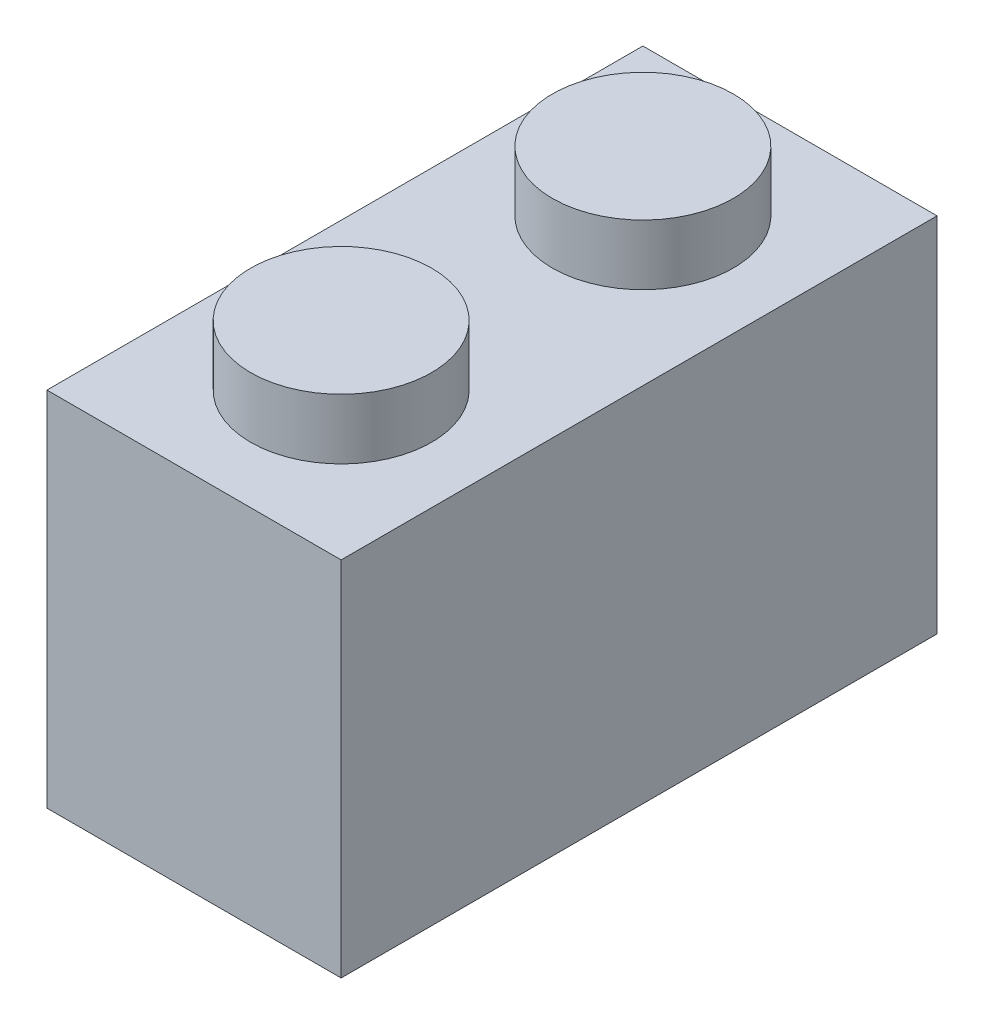
SolidWorks part; units mm, degrees
material "ABS"
ref_plane "Front Plane" through (0, 0, 0) normal (0, 0, 1) x (1, 0, 0)
ref_plane "Top Plane" through (0, 0, 0) normal (0, 1, 0) x (1, 0, 0)
ref_plane "Right Plane" through (0, 0, 0) normal (1, 0, 0) x (0, 0, -1)
sketch "Sketch1" plane through (0, 0, 0) normal (0, 0, 1) x (1, 0, 0)
  line L1 (0, 0) -> (7.8, 0)
  line L2 (0, 0) -> (0, 9.6)
  line L3 (0, 9.6) -> (7.8, 9.6)
  line L4 (7.8, 0) -> (7.8, 9.6)
  line L5 (0, 0) -> (7.8, 9.6) construction
  line L6 (0, 9.6) -> (7.8, 0) construction
  point P4 (3.9, 4.8)
  dimension "D1" = 7.8
  dimension "D2" = 9.6
extrude "Boss-Extrude1" add sketch "Sketch1" against normal blind 15.8
sketch "Sketch2" plane through (0, 9.6, 0) normal (0, 1, 0) x (1, 0, 0)
  line L0 (7.8, 0) -> (0, 0) construction
  circle A0 centre (3.9, 3.9) radius 2.4
  dimension "D1" = 4.8
  dimension "D2" = 3.9
  dimension "D3" = 3.9
extrude "Boss-Extrude2" add sketch "Sketch2" along normal blind 1.6
pattern_linear "LPattern1" count 2 spacing 8 along (0, 0, -1) count 4 spacing 8 along (-1, 0, 0) of "Boss-Extrude2"
shell "Shell1" thickness 1.2
sketch "Sketch4" plane through (0, 8.4, 0) normal (0, -1, 0) x (1, 0, 0)
  line L0 (0, -15.8) -> (0, 0) construction
  line L1 (0, 0) -> (7.8, 0) construction
  circle A0 centre (7.9, -7.9) radius 3.25
  circle A1 centre (7.9, -7.9) radius 2.4
  dimension "D1" = 4.8
  dimension "D2" = 6.5
  dimension "D3" = 7.9
  dimension "D4" = 7.9
extrude "Boss-Extrude3" [suppressed] add sketch "Sketch4" along normal offset from surface (8.2 mm away) 0.2
sketch "Sketch5" plane through (0, 8.4, 0) normal (0, -1, 0) x (1, 0, 0)
  line L0 (0, -15.8) -> (0, 0) construction
  line L1 (0, 0) -> (7.8, 0) construction
  circle A0 centre (3.9, -7.9) radius 1.5
  point P4 (0, 0)
  dimension "D1" = 3
  dimension "D2" = 3.9
  dimension "D3" = 7.9
extrude "Boss-Extrude4" add sketch "Sketch5" along normal offset from surface (8.2 mm away) 0.2 up to face at (3.9, 0, -7.9)
